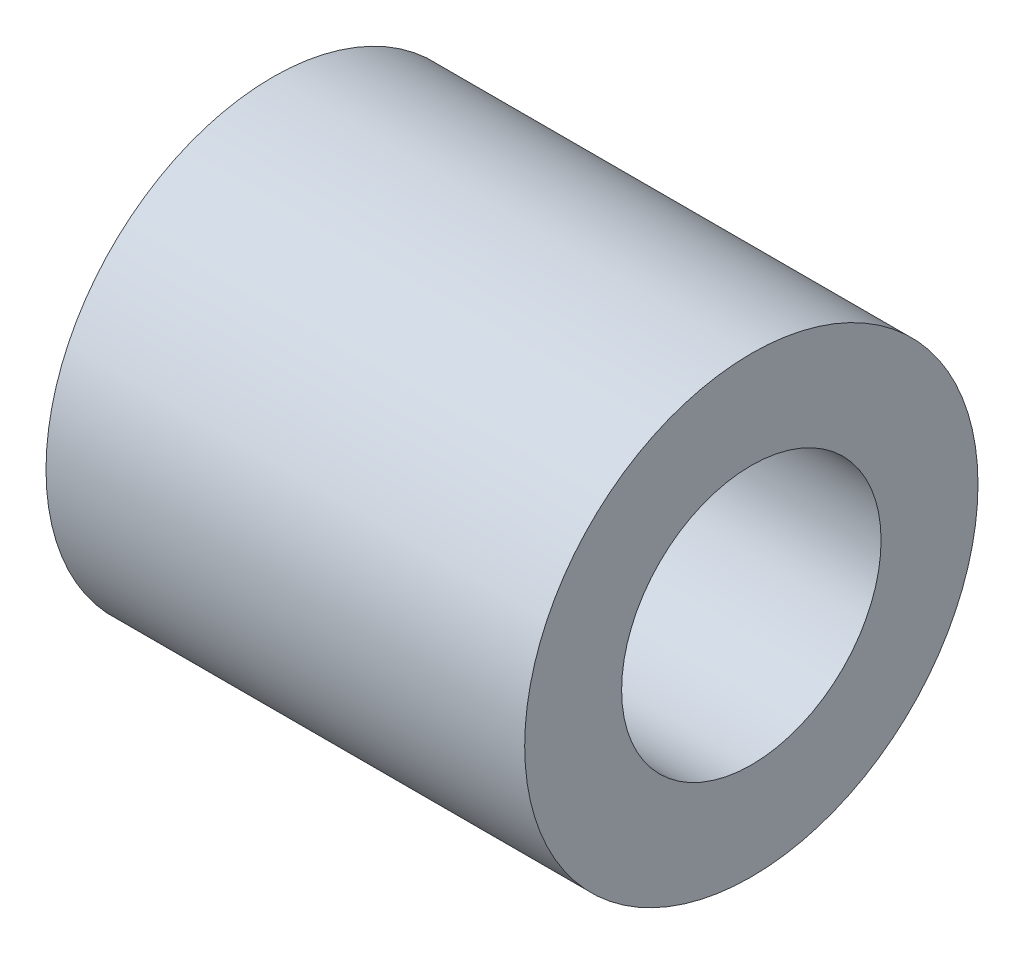
SolidWorks part; units mm, degrees
ref_plane "Ebene vorne" through (0, 0, 0) normal (0, 0, 1) x (1, 0, 0)
ref_plane "Ebene oben" through (0, 0, 0) normal (0, 1, 0) x (1, 0, 0)
ref_plane "Ebene rechts" through (0, 0, 0) normal (1, 0, 0) x (0, 0, -1)
sketch "Sketch1" plane through (0, 0, 0) normal (1, 0, 0) x (0, 0, -1)
  circle A0 centre (0, 0) radius 27.1
  circle A1 centre (0, 0) radius 47.35
  dimension "D1" = 54.2
  dimension "D2" = 94.7
extrude "Boss-Extrude1" add sketch "Sketch1" along normal blind 100
